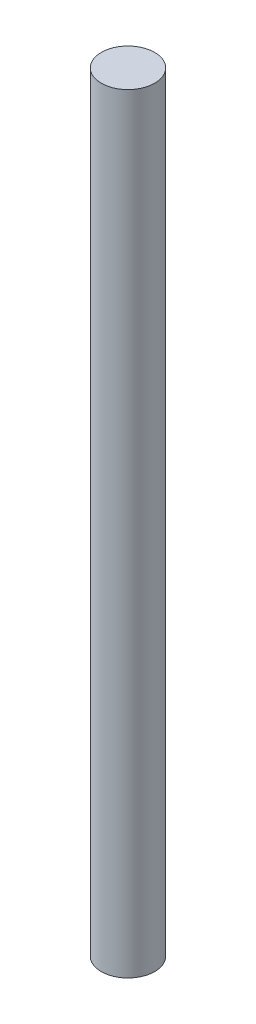
SolidWorks part; units mm, degrees
ref_plane "Płaszczyzna przednia" through (0, 0, 0) normal (0, 0, 1) x (1, 0, 0)
ref_plane "Płaszczyzna górna" through (0, 0, 0) normal (0, 1, 0) x (1, 0, 0)
ref_plane "Płaszczyzna prawa" through (0, 0, 0) normal (1, 0, 0) x (0, 0, -1)
sketch "Szkic1" plane through (0, 0, 0) normal (0, 1, 0) x (1, 0, 0)
  circle A0 centre (0, 0) radius 2.5
  dimension "D1" = 5
extrude "Dodanie-wyciągnięcie1" add sketch "Szkic1" along normal blind 72.03
